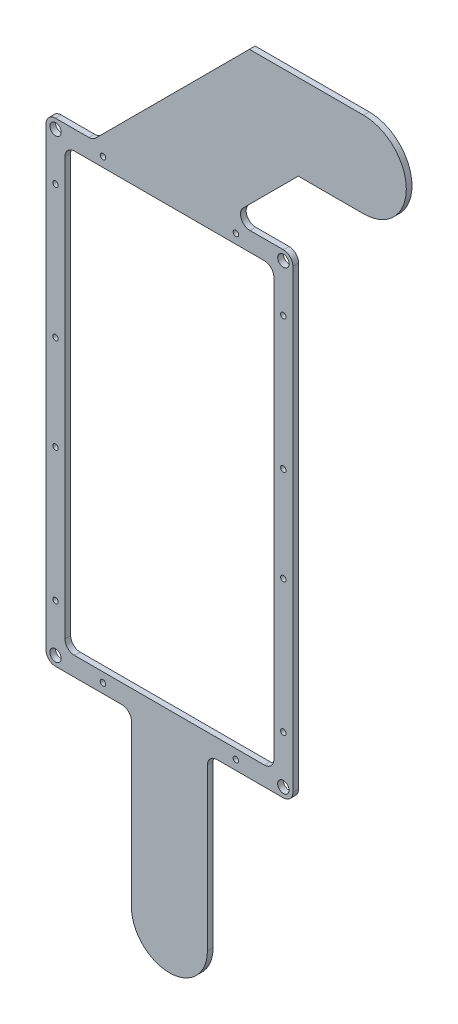
SolidWorks part; units mm, degrees
ref_plane "Front Plane" through (0, 0, 0) normal (0, 0, 1) x (1, 0, 0)
ref_plane "Top Plane" through (0, 0, 0) normal (0, 1, 0) x (1, 0, 0)
ref_plane "Right Plane" through (0, 0, 0) normal (1, 0, 0) x (0, 0, -1)
sketch "Sketch1" plane through (0, 0, 0) normal (0, 0, 1) x (1, 0, 0)
  line L1 (-60, -125) -> (60, -125)
  line L2 (-65, -120) -> (-65, 120)
  line L3 (-60, 125) -> (60, 125)
  line L4 (65, -120) -> (65, 120)
  line L5 (-65, -125) -> (65, 125) construction
  line L6 (-65, 125) -> (65, -125) construction
  line L8 (60, 125) -> (-60, 125) construction
  line L9 (-50, -115) -> (50, -115)
  line L10 (-55, -110) -> (-55, 110)
  line L11 (-50, 115) -> (50, 115)
  line L12 (55, -110) -> (55, 110)
  line L13 (-55, -115) -> (55, 115) construction
  line L14 (-55, 115) -> (55, -115) construction
  line L15 (-65, 120) -> (-65, -120) construction
  line L16 (65, -120) -> (65, 120) construction
  line L17 (-60, -125) -> (60, -125) construction
  arc A0 (60, -125) -> (65, -120) centre (60, -120) ccw
  arc A1 (-60, -125) -> (-65, -120) centre (-60, -120) cw
  arc A2 (-65, 120) -> (-60, 125) centre (-60, 120) cw
  arc A3 (60, 125) -> (65, 120) centre (60, 120) cw
  circle A7 centre (-60, 120) radius 3
  circle A9 centre (60, 120) radius 3
  circle A11 centre (-60, -120) radius 3
  circle A13 centre (60, -120) radius 3
  arc A15 (-50, -115) -> (-55, -110) centre (-50, -110) cw
  arc A16 (50, -115) -> (55, -110) centre (50, -110) ccw
  arc A17 (50, 115) -> (55, 110) centre (50, 110) cw
  arc A18 (-55, 110) -> (-50, 115) centre (-50, 110) cw
  arc A19 (-60, 125) -> (-65, 120) centre (-60, 120) ccw construction
  arc A20 (65, 120) -> (60, 125) centre (60, 120) ccw construction
  point P0 (0, 0)
  point P5 (0, 0)
  point P41 (0, 0)
  dimension "D1" = 6
  dimension "D4" = 5
  dimension "D2" = 10
  dimension "D3" = 10
extrude "Boss-Extrude1" add sketch "Sketch1" along normal blind 10
sketch "Sketch2" plane through (0, 0, 0) normal (0, 0, -1) x (-1, 0, 0)
  line L0 (-38.6084, 120) -> (-31.3916, 120) construction
  line L1 (-60, 98.6084) -> (-60, 91.3916) construction
  line L2 (-60, 28.6084) -> (-60, 21.3916) construction
  line L3 (-65, 0) -> (65, 0) construction
  line L4 (-65, -120) -> (-65, 120) construction
  line L5 (65, 120) -> (65, -120) construction
  line L6 (-60, -28.6084) -> (-60, -21.3916) construction
  line L7 (-60, -98.6084) -> (-60, -91.3916) construction
  line L8 (-38.6084, -120) -> (-31.3916, -120) construction
  line L9 (0, 0) -> (0, 125) construction
  line L10 (-60, 125) -> (60, 125) construction
  line L11 (38.6084, -120) -> (31.3916, -120) construction
  line L12 (60, -98.6084) -> (60, -91.3916) construction
  line L13 (60, -28.6084) -> (60, -21.3916) construction
  line L14 (60, 28.6084) -> (60, 21.3916) construction
  line L15 (60, 98.6084) -> (60, 91.3916) construction
  line L16 (38.6084, 120) -> (31.3916, 120) construction
  circle A0 centre (-35, 120) radius 1.45
  circle A1 centre (-60, 95) radius 1.45
  circle A2 centre (-60, 25) radius 1.45
  circle A3 centre (-60, -25) radius 1.45
  circle A4 centre (-60, -95) radius 1.45
  circle A5 centre (-35, -120) radius 1.45
  circle A6 centre (35, -120) radius 1.45
  circle A7 centre (60, -95) radius 1.45
  circle A8 centre (60, -25) radius 1.45
  circle A9 centre (60, 25) radius 1.45
  circle A10 centre (60, 95) radius 1.45
  circle A11 centre (35, 120) radius 1.45
  dimension "D1" = 2.9
extrude "Cut-Extrude1" cut sketch "Sketch2" against normal through all
sketch "Sketch3" plane through (0, 0, 10) normal (0, 0, 1) x (1, 0, 0)
  line L0 (-20, -214.79) -> (-20, -130)
  line L1 (-60, -125) -> (60, -125) construction
  line L2 (-25, -125) -> (25, -125)
  line L3 (0, -125) -> (0, -234.79) construction
  line L7 (20, -214.79) -> (20, -130)
  arc A0 (-20, -214.79) -> (20, -214.79) centre (0, -214.79) ccw
  arc A2 (-20, -130) -> (-25, -125) centre (-25, -130) ccw
  arc A3 (20, -130) -> (25, -125) centre (25, -130) cw
  point P9 (0, -125)
  dimension "D2" = 40
  dimension "D3" = 89.79
  dimension "D4" = 5
extrude "Boss-Extrude2" add sketch "Sketch3" against normal through all
sketch "Sketch4" plane through (0, 0, 10) normal (0, 0, 1) x (1, 0, 0)
  line L0 (-50, -115) -> (50, -115) construction
  line L2 (0, -115) -> (0, -141.1166) construction
  line L3 (17.5, -115) -> (-17.5, -115)
  line L5 (-12.5, -214.79) -> (-12.5, -120)
  line L6 (12.5, -214.79) -> (12.5, -120)
  arc A0 (-12.5, -120) -> (-17.5, -115) centre (-17.5, -120) ccw
  arc A1 (12.5, -120) -> (17.5, -115) centre (17.5, -120) cw
  arc A2 (-12.5, -214.79) -> (12.5, -214.79) centre (0, -214.79) ccw
  point P15 (0, -125)
  dimension "D1" = 12.5
  dimension "D2" = 5
extrude "Cut-Extrude2" [suppressed] cut sketch "Sketch4" against normal through all
sketch "Sketch5" plane through (0, 0, 10) normal (0, 0, 1) x (1, 0, 0)
  line L0 (-42.4264, 125) -> (42.4264, 125)
  line L2 (60, 125) -> (-60, 125) construction
  line L6 (0, 125) -> (0, 133.7618) construction
  line L7 (102.25, 207.5) -> (42.1447, 207.5)
  line L8 (42.1447, 207.5) -> (-38.8909, 126.4645)
  line L10 (102.25, 162.5) -> (67.8553, 162.5)
  line L11 (67.8553, 162.5) -> (38.8909, 133.5355)
  arc A1 (102.25, 162.5) -> (102.25, 207.5) centre (102.25, 185) ccw
  arc A2 (-42.4264, 125) -> (-38.8909, 126.4645) centre (-42.4264, 130) ccw
  arc A3 (38.8909, 133.5355) -> (42.4264, 125) centre (42.4264, 130) ccw
  point P1 (0, 125)
  dimension "D3" = 22.5
  dimension "D6" = 45
  dimension "D9" = 10
  dimension "D10" = 10
  dimension "D2" = 50
  dimension "D4" = 102.25
  dimension "D5" = 60
extrude "Boss-Extrude3" add sketch "Sketch5" against normal blind 10
sketch "Sketch7" plane through (0, 0, 10) normal (0, 0, 1) x (1, 0, 0)
  line L0 (102.25, 197.5) -> (46.2868, 197.5)
  line L1 (46.2868, 197.5) -> (-25, 126.2132)
  line L2 (50, 115) -> (-50, 115) construction
  line L3 (-25, 115) -> (25, 115)
  line L4 (25, 133.7868) -> (63.7132, 172.5)
  line L5 (63.7132, 172.5) -> (102.25, 172.5)
  line L6 (67.8553, 162.5) -> (38.8909, 133.5355) construction
  line L7 (42.1447, 207.5) -> (-38.8909, 126.4645) construction
  line L8 (-25, 126.2132) -> (-25, 115)
  line L11 (25, 133.7868) -> (25, 115)
  arc A0 (102.25, 172.5) -> (102.25, 197.5) centre (102.25, 185) ccw
  point P9 (0, 115)
  dimension "D1" = 25
  dimension "D2" = 10
  dimension "D3" = 10
  dimension "D4" = 50
extrude "Cut-Extrude4" [suppressed] cut sketch "Sketch7" against normal through all
sketch "Sketch8" plane through (-65, 0, 0) normal (-1, 0, 0) x (0, 0, 1)
  line L0 (0, 207.5) -> (0, 126.4645) construction
  line L1 (65.7311, 217.5111) -> (3, 217.5111)
  line L2 (65.7311, 217.5111) -> (65.7311, -249.5454)
  line L3 (65.7311, -249.5454) -> (3, -249.5454)
  line L4 (3, 217.5111) -> (3, -249.5454)
  dimension "D1" = 3
extrude "Cut-Extrude5" cut sketch "Sketch8" against normal through all
equation "\"X-ROD-SPACING\"=45"
equation "\"Y-ROD-SPACING\"=75"
equation "\"Z-ROD-SPACING\"=17.5"
equation "\"Y-BED-OFFSET\"=2"
equation "\"Y-BED-ROD-INSET\"=3.5"
equation "\"Y-BED-SCREW-SPACING\"=209"
equation "\"Y-BED-SCREW-CUTOUT-SLOT-HEIGHT\"=2.5"
equation "\"T-SLOT-NUT-FILLET-RADIUS\"=0.5"
equation "\"T-SLOT-SCREW-SHAFT-RADIUS\"=1.55"
equation "\"T-SLOT-SCREW-SHAFT-CUTOUT-LENGTH\"=11"
equation "\"T-SLOT-NUT-DEPTH\"=3.5"
equation "\"T-SLOT-NUT-WIDTH\"=2.85"
equation "\"T-SLOT-NUT-END-DISTANCE\"=8"
equation "\"ACRYLIC-THICKNESS\"=10"
equation "\"ACRYLIC-THICKNESS2\"=4.5"
equation "\"ACRYLIC-TAB-CUTOUT-SIZE\"=\"ACRYLIC-THICKNESS\"+\"ACRYLIC-TAB-TOLERANCE\"*2"
equation "\"ACRYLIC-TAB-TOLERANCE\"=-.05"
equation "\"KERF\"=0.075"
equation "\"ACRYLIC-THICKNESS-TAB-CUTOUT-WIDTH\"=\"ACRYLIC-THICKNESS\"-\"KERF\"*2"
equation "\"ACRYLIC-THICKNESS-TAB-CUTOUT-HEIGHT\"=\"ACRYLIC-TAB-WIDTH\"-\"KERF\"*4"
equation "\"ACRYLIC-THICKNESS2-TAB-CUTOUT-WIDTH\"=\"ACRYLIC-THICKNESS2\"-\"KERF\"*2"
equation "\"ACRYLIC-THICKNESS2-TAB-CUTOUT-HEIGHT\"=\"ACRYLIC-TAB-WIDTH\"-\"KERF\"*4"
equation "\"ACRYLIC-TAB-WIDTH\"=\"ACRYLIC-THICKNESS\""
equation "\"ACRYLIC-M3-HOLE\"=2.9"
equation "\"ACRYLIC-M4-HOLE\"=3.9"
equation "\"SMOOTHROD-CAP-SCREW-DISTANCE\"=20"
equation "\"FRAME-WIDTH-INNER\"=370"
equation "\"NEMA17-HOLE-SPACING\"=31"
equation "\"NEMA17-CENTRAL-CUTOUT\"=22.5"
equation "\"Z-BRACKET-REACH\"=57"
equation "\"Z-ROD-INSET\"=13.5"
equation "\"TOP-BRACKET-SPACING\"=40"
equation "\"SMOOTHROD-X-LENGTH\"=350"
equation "\"SMOOTHROD-Y-LENGTH\"=350"
equation "\"SMOOTHROD-Z-LENGTH\"=350"
equation "\"SMOOTHROD-TIGHTENING-HEADROOM\"=.25"
equation "\"LEADSCREW-Z-LENGTH\"=300"
equation "\"SCREW-LENGTH-FRAME\"=\"ACRYLIC-THICKNESS\" + 10"
equation "\"SCREW-LENGTH-MOTOR\"=\"ACRYLIC-THICKNESS\" + 5"
equation "\"SCREW-LENGTH-EXTRUDER\"=28"
equation "\"SCREW-HEAD-RADIUS\"=6"
equation "\"PRINTED-M3-HOLE\"=3.5"
equation "\"PRINTED-X-SMOOTHROD-DIAMETER\"=8.8"
equation "\"PRINTED-X-SMOOTHROD-CUTOUT\"=10"
equation "\"PRINTED-X-BASE-HEIGHT\"=10"
equation "\"PRINTED-LM8UU-CUTOUT-SIZE\"=15.5"
equation "\"PRINTED-LM8UU-CUTOUT-LENGTH\"=24.5"
equation "\"PRINTED-X-IDLER-HEIGHT\"=16"
equation "\"PRINTED-M3-NUT-AF\"=6.25"
equation "\"PSU-MOUNTING-WIDTH\"=50"
equation "\"PSU-MOUNTING-HEIGHT\"=150"
equation "\"Y-BELT-TO-ROD-DISTANCE\"=20"
equation "\"SPOOL-HOLDER-ROD-SPACING\"=150"
equation "\"ACRYLIC-X-CARRIAGE-WIDTH\"=55"
equation "\"ACRYLIC-X-CARRIAGE-HEIGHT\"=75"
equation "\"ACRYLIC-X-CARRIAGE-LM8UU-CUTOUT-WIDTH\"=24.25"
equation "\"ACRYLIC-X-CARRIAGE-LM8UU-CUTOUT-HEIGHT\"=11.0"
equation "\"ACRYLIC-X-CARRIAGE-SCREW-SPACING-X\"=15"
equation "\"ACRYLIC-X-CARRIAGE-SCREW-SPACING-Y\"=33"
equation "\"ACRYLIC-X-CARRIAGE-CENTER-TAB-SPACING\"=14"
equation "\"ACRYLIC-X-CARRIAGE-EXTRUDER-OFFSET\"=26"
equation "\"ACRYLIC-X-CARRIAGE-EXTRUDER-ANGLE\"=90"
equation "\"ACRYLIC-X-CARRIAGE-EXTRUDER-SHELF-DEPTH\"=\"ACRYLIC-X-CARRIAGE-EXTRUDER-OFFSET\" + 28"
equation "\"ACRYLIC-X-CARRIAGE-EXTRUDER-BRACE-SPACING\"=23"
equation "\"ACRYLIC-X-CARRIAGE-EXTRUDER-BRACE-TAB-OFFSET\"=20"
equation "\"ACRYLIC-X-CARRIAGE-EXTRUDER-BRACE-HEIGHT\"=35"
equation "\"ACRYLIC-X-CARRIAGE-EXTRUDER-BRACE-SCREW-SPACING\"=22"
equation "\"ACRYLIC-X-CARRIAGE-DUAL-WIDTH-MULTIPLIER\"=1.65"
equation "\"ACRYLIC-X-CARRIAGE-DUAL-HOTEND-SPACING\"=42"
equation "\"ACRYLIC-X-CARRIAGE-DUAL-WIDTH\"=75"
equation "\"ACRYLIC-X-CARRIAGE-DUAL-FAN-OFFSET\"=52"
equation "\"ACRYLIC-X-CARRIAGE-DUAL-FAN-HEIGHT\"=20"
equation "\"ACRYLIC-X-CARRIAGE-DUAL-HOTEND-SEPARATION\"=36"
equation "\"ACRYLIC-X-CARRIAGE-DUAL-MOUNT-PLATE-DEPTH\"=75"
equation "\"ACRYLIC-X-CARRIAGE-DUAL-MOUNT-BRACE-WIDTH\"=33"
equation "\"ACRYLIC-X-CARRIAGE-DUAL-MOUNT-SCREW-WIDTH\"=40"
equation "\"BLOWER-FAN-WIDTH\"=15"
equation "\"D1@Sketch2\"=\"ACRYLIC-M3-HOLE\""
